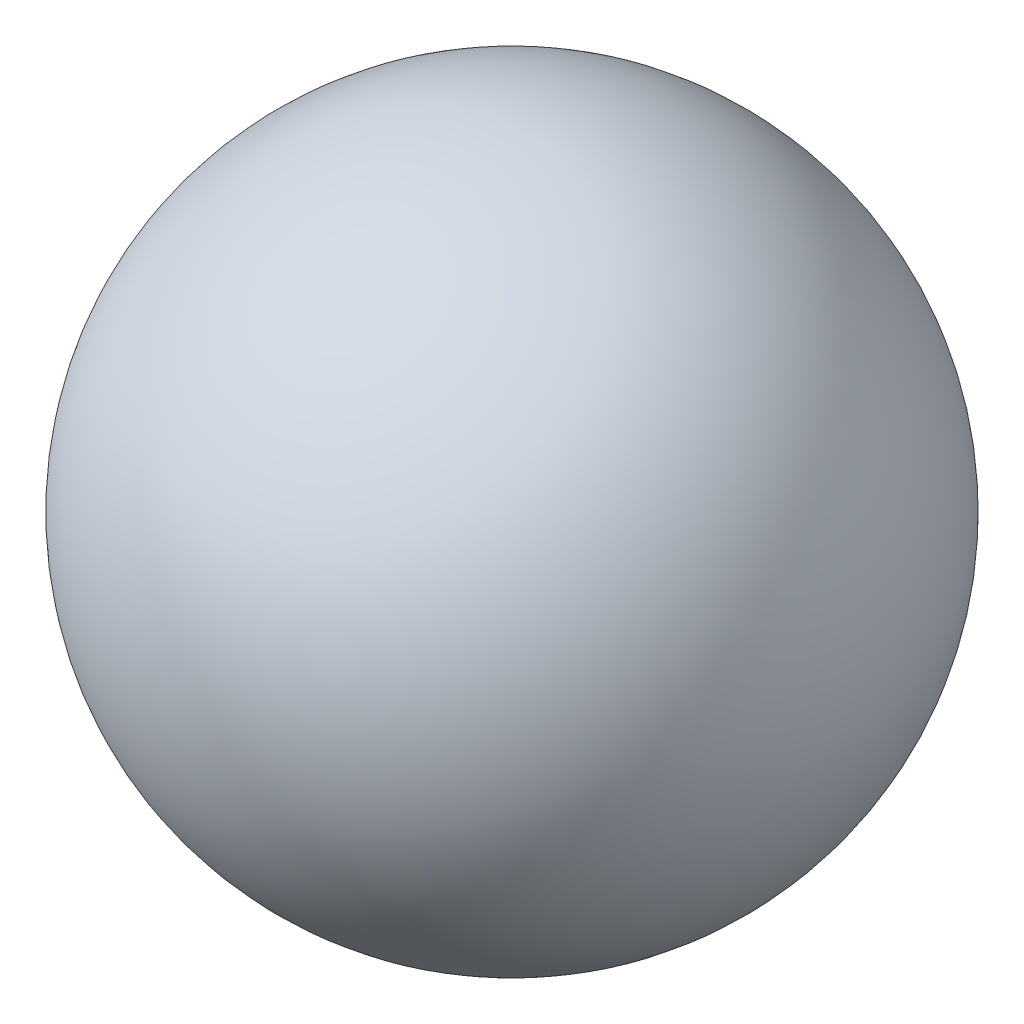
SolidWorks part; units mm, degrees
ref_plane "Front Plane" through (0, 0, 0) normal (0, 0, 1) x (1, 0, 0)
ref_plane "Top Plane" through (0, 0, 0) normal (0, 1, 0) x (1, 0, 0)
ref_plane "Right Plane" through (0, 0, 0) normal (1, 0, 0) x (0, 0, -1)
sketch "Sketch1" plane through (0, 0, 0) normal (1, 0, 0) x (0, 0, -1)
  line L0 (0, 22.225) -> (0, -22.225)
  arc A0 (0, 22.225) -> (0, -22.225) centre (0, 0) cw
  point P4 (0, 0)
  dimension "D1" = 44.45
revolve "Revolve1" add sketch "Sketch1" angle 360 about L0
